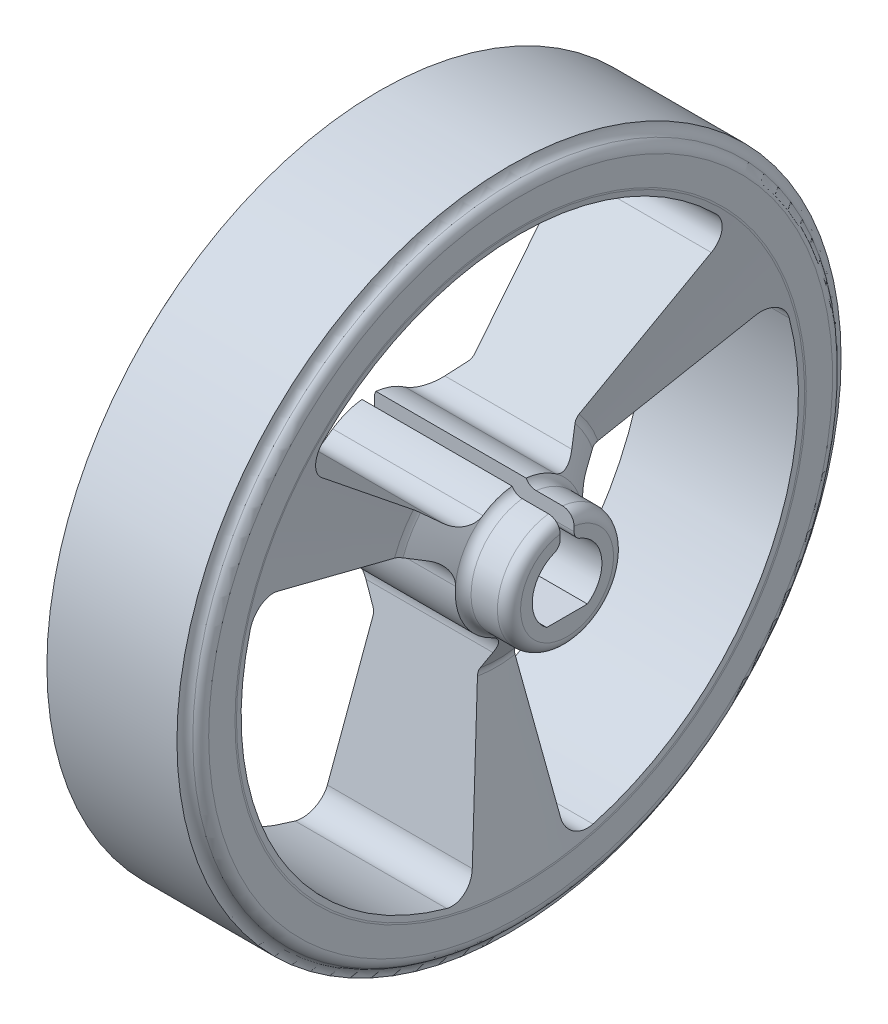
SolidWorks part; units mm, degrees
material "PBT General Purpose"
ref_plane "Front" through (0, 0, 0) normal (0, 0, 1) x (1, 0, 0)
ref_plane "Top" through (0, 0, 0) normal (0, 1, 0) x (1, 0, 0)
ref_plane "Right" through (0, 0, 0) normal (1, 0, 0) x (0, 0, -1)
sketch "Sketch1" plane through (0, 0, 0) normal (0, 1, 0) x (1, 0, 0)
  line L0 (0, 0) -> (14.3, 0) construction
  line L1 (0, 0) -> (0, 2.5)
  line L2 (0.067, 2.75) -> (0.9877, 4.3447)
  line L3 (0, 12.3) -> (0, 13.434)
  line L4 (0.5, 14.3) -> (6.1, 14.3)
  line L5 (3.3, 14.3) -> (3.3, 0) construction
  line L6 (1.05, 4.6632) -> (0.0047, 12.2316)
  line L7 (5.55, 4.6632) -> (6.5953, 12.2316)
  line L8 (6.6, 12.3) -> (6.6, 13.434)
  line L9 (6.533, 2.75) -> (5.6123, 4.3447)
  line L10 (6.966, 2.5) -> (8.1, 2.5)
  line L11 (8.6, 2) -> (8.6, 0)
  line L12 (0, 0) -> (8.6, 0)
  arc A0 (0, 2.5) -> (0.067, 2.75) centre (0.5, 2.5) cw
  arc A1 (0.9877, 4.3447) -> (1.05, 4.6632) centre (0.5547, 4.5947) ccw
  arc A2 (0.0047, 12.2316) -> (0, 12.3) centre (0.5, 12.3) cw
  arc A3 (0, 13.434) -> (0.25, 13.867) centre (0.5, 13.434) cw
  arc A4 (0.25, 13.867) -> (0.5, 14.3) centre (0, 14.3) ccw
  arc A5 (6.35, 13.867) -> (6.1, 14.3) centre (6.6, 14.3) cw
  arc A6 (6.6, 13.434) -> (6.35, 13.867) centre (6.1, 13.434) ccw
  arc A7 (6.5953, 12.2316) -> (6.6, 12.3) centre (6.1, 12.3) ccw
  arc A8 (5.6123, 4.3447) -> (5.55, 4.6632) centre (6.0453, 4.5947) cw
  arc A9 (6.533, 2.75) -> (6.966, 2.5) centre (6.966, 3) ccw
  arc A10 (8.1, 2.5) -> (8.6, 2) centre (8.1, 2) cw
  dimension "D1" = 28.6
  dimension "D2" = 0.5
  dimension "D3" = 6.6
  dimension "D4" = 5
  dimension "D5" = 4.5
  dimension "D6" = 2
  dimension "D7" = 30
  dimension "D8" = 8.6
revolve "Revolve1" add sketch "Sketch1" angle 360 about L12
sketch "Sketch2" plane through (0, 0, 0) normal (1, 0, 0) x (0, 0, -1)
  line L0 (0, 0) -> (0, 12) construction
  line L1 (8.3916, 7.0414) -> (2.7686, 2.3232)
  line L2 (0, 0) -> (10.3923, 6) construction
  line L3 (0, 0) -> (10.3923, -6) construction
  line L4 (0, 0) -> (0, -12) construction
  line L5 (0, 0) -> (-10.3923, -6) construction
  line L6 (0, 0) -> (-10.3923, 6) construction
  line L7 (-8.3916, 7.0414) -> (-2.7686, 2.3232)
  arc A0 (-2.7686, 2.3232) -> (-1.559, 2.2654) centre (-2.1259, 3.0892) ccw
  arc A1 (-8.4532, 8.5172) -> (8.4532, 8.5172) centre (0, 0) cw
  arc A2 (8.4532, 8.5172) -> (8.3916, 7.0414) centre (7.7488, 7.8074) cw
  arc A3 (-8.4532, 8.5172) -> (-8.3916, 7.0414) centre (-7.7488, 7.8074) ccw
  arc A4 (2.7686, 2.3232) -> (1.559, 2.2654) centre (2.1259, 3.0892) cw
  arc A5 (1.559, 2.2654) -> (-1.559, 2.2654) centre (0, 0) ccw
  circle A6 centre (0, 0) radius 2.75 construction
  point P19 (0, 0)
  dimension "D1" = 12
  dimension "D2" = 6
  dimension "D4" = 1
  dimension "D3" = 50
extrude "Cut-Extrude2" cut sketch "Sketch2" against normal through all and the other way through all
pattern_circular "CirPattern1" count 3 over 360 about axis through (0, 0, 0) along (1, 0, 0) of "Cut-Extrude2"
sketch "Sketch3" plane through (0, 0, 0) normal (-1, 0, 0) x (0, 0, 1)
  line L0 (0.875, -1.2183) -> (-0.875, -1.2183)
  line L1 (0.3, 1.7664) -> (0.3, 2.7336)
  line L2 (0, 0) -> (0, 2.75) construction
  line L3 (-0.3, 1.7664) -> (-0.3, 2.7336)
  arc A0 (0.875, -1.2183) -> (0.5526, 1.3945) centre (0, 0) ccw
  arc A1 (0.5526, 1.3945) -> (0.3, 1.7664) centre (0.7, 1.7664) cw
  arc A2 (1.559, 2.2654) -> (-1.559, 2.2654) centre (0, 0) ccw construction
  arc A3 (0.3, 2.7336) -> (-0.3, 2.7336) centre (0, 0) ccw
  arc A4 (-0.875, -1.2183) -> (-0.5526, 1.3945) centre (0, 0) cw
  arc A5 (-0.5526, 1.3945) -> (-0.3, 1.7664) centre (-0.7, 1.7664) ccw
  point P12 (0, -1.2183)
  dimension "D1" = 1.5
  dimension "D3" = 0.4
  dimension "D2" = 0.6
  dimension "D4" = 1.75
extrude "Cut-Extrude3" cut sketch "Sketch3" against normal through all
scale "Scale1" scale about centroid uniform scaling yes scale factor 4
